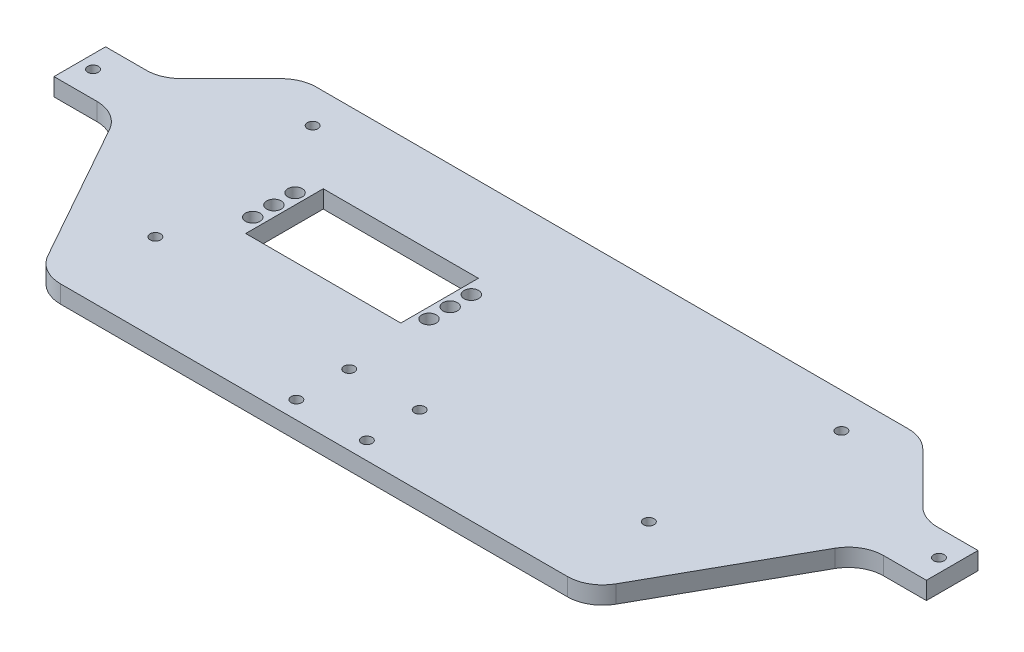
SolidWorks part; units mm, degrees
ref_plane "Alzado" through (0, 0, 0) normal (0, 0, 1) x (1, 0, 0)
ref_plane "Planta" through (0, 0, 0) normal (0, 1, 0) x (1, 0, 0)
ref_plane "Vista lateral" through (0, 0, 0) normal (1, 0, 0) x (0, 0, -1)
sketch "Croquis1" plane through (0, 0, 0) normal (0, 1, 0) x (1, 0, 0)
  line L0 (-27.8825, 0) -> (38.5584, 0) construction
  line L1 (-88.1, 42.3182) -> (88.1, 42.3182)
  line L2 (-77.75, -42.3182) -> (77.75, -42.3182)
  line L3 (-88.1, 42.3182) -> (-108.1, 22.3182)
  line L4 (-108.1, 22.3182) -> (-127.75, 22.3182)
  line L5 (0, 0) -> (0, 27.7067) construction
  line L6 (-127.75, 22.3182) -> (-127.75, 7.6818)
  line L7 (-127.75, 7.6818) -> (-105.75, 7.6818)
  line L8 (-105.75, 7.6818) -> (-77.75, -42.3182)
  line L9 (88.1, 42.3182) -> (108.1, 22.3182)
  line L10 (108.1, 22.3182) -> (127.75, 22.3182)
  line L11 (127.75, 22.3182) -> (127.75, 7.6818)
  line L12 (127.75, 7.6818) -> (105.75, 7.6818)
  line L13 (105.75, 7.6818) -> (77.75, -42.3182)
  dimension "D1" = 255.5
  dimension "D2" = 84.6363
  dimension "D3" = 19.65
  dimension "D4" = 22
  dimension "D5" = 22
  dimension "D6" = 50
  dimension "D7" = 50
  dimension "D8" = 50
  dimension "D9" = 20
  dimension "D10" = 20
  dimension "D11" = 19.65
extrude "Saliente-Extruir1" add sketch "Croquis1" along normal blind 5
fillet "Redondeo1" radius 10 8 edges at (88.1, 2.5, -42.3182) (-88.1, 2.5, -42.3182) (-77.75, 2.5, 42.3182) (77.75, 2.5, 42.3182) (108.1, 2.5, -22.3182) (105.75, 2.5, -7.6818) (-105.75, 2.5, -7.6818) (-108.1, 2.5, -22.3182)
sketch "Croquis2" plane through (0, 5, 0) normal (0, 1, 0) x (1, 0, 0)
  line L0 (0, 0) -> (0, -87.7887) construction
  line L1 (-119.9961, 22.3182) -> (-119.9961, 40.4374) construction
  line L2 (-112.2421, 22.3182) -> (-127.75, 22.3182) construction
  line L3 (-127.75, 15) -> (-123.2915, 15) construction
  line L4 (-127.75, 22.3182) -> (-127.75, 7.6818) construction
  line L5 (119.9961, 22.3182) -> (119.9961, 29.1715) construction
  line L6 (127.75, 22.3182) -> (112.2421, 22.3182) construction
  line L7 (115.6048, 15) -> (126.3231, 15) construction
  line L8 (83.9579, 42.3182) -> (-83.9579, 42.3182) construction
  line L9 (-57, 17.3182) -> (-15, 17.3182)
  line L10 (-71.8888, -42.3182) -> (71.8888, -42.3182) construction
  line L11 (-15, 17.3182) -> (-15, -2.6818)
  line L12 (-15, -2.6818) -> (-57, -2.6818)
  line L13 (-57, -2.6818) -> (-57, 17.3182)
  line L14 (-57, 7.3182) -> (-2.6959, 7.3182) construction
  line L15 (-36, 17.3182) -> (-36, 33.9331) construction
  line L16 (-11, 7.3182) -> (-11, 14.1752) construction
  line L17 (-61, 7.3182) -> (-61, 4.4352) construction
  circle A0 centre (70, -17.3182) radius 1.5
  circle A1 centre (-70, -17.3182) radius 1.5
  circle A2 centre (-119.9961, 15) radius 1.5
  circle A3 centre (119.9961, 15) radius 1.5
  circle A4 centre (-75, 32.3182) radius 1.5
  circle A5 centre (75, 32.3182) radius 1.5
  circle A6 centre (-10, -22.3182) radius 1.5
  circle A7 centre (10, -22.3182) radius 1.5
  circle A8 centre (-10, -37.3182) radius 1.5
  circle A9 centre (10, -37.3182) radius 1.5
  circle A10 centre (-61, 7.3182) radius 2.05
  circle A11 centre (-11, 7.3182) radius 2.05
  circle A12 centre (-61, 13.3182) radius 2.05
  circle A13 centre (-61, 1.3182) radius 2.05
  circle A14 centre (-11, 13.3182) radius 2.05
  circle A15 centre (-11, 1.3182) radius 2.05
  dimension "D1" = 3
  dimension "D2" = 3
  dimension "D7" = 3
  dimension "D8" = 3
  dimension "D10" = 3
  dimension "D11" = 3
  dimension "D17" = 3
  dimension "D18" = 3
  dimension "D19" = 3
  dimension "D20" = 3
  dimension "D25" = 50
  dimension "D27" = 4.1
  dimension "D28" = 4.1
  dimension "D29" = 4.1
  dimension "D30" = 4.1
  dimension "D31" = 4.1
  dimension "D32" = 4.1
  dimension "D3" = 75
  dimension "D4" = 75
  dimension "D5" = 10
  dimension "D6" = 10
  dimension "D9" = 140
  dimension "D12" = 25
  dimension "D13" = 20
  dimension "D14" = 20
  dimension "D15" = 5
  dimension "D16" = 15
  dimension "D21" = 42
  dimension "D22" = 20
  dimension "D23" = 30
  dimension "D24" = 25
  dimension "D26" = 50
  dimension "D33" = 6
  dimension "D34" = 6
  dimension "D35" = 6
  dimension "D36" = 6
extrude "Cortar-Extruir1" cut sketch "Croquis2" against normal through all
sketch "Croquis3" plane through (0, 5, 0) normal (0, 1, 0) x (1, 0, 0)
  line L0 (-123.75, 22.3182) -> (-123.75, 7.6818)
  line L1 (-112.2421, 22.3182) -> (-127.75, 22.3182) construction
  line L2 (-127.75, 7.6818) -> (-111.6112, 7.6818) construction
  line L3 (-123.75, 7.6818) -> (-127.75, 7.6818)
  line L4 (-127.75, 7.6818) -> (-127.75, 22.3182)
  line L5 (-127.75, 22.3182) -> (-123.75, 22.3182)
  line L6 (127.75, 7.6818) -> (127.75, 22.3182)
  line L7 (127.75, 22.3182) -> (123.75, 22.3182)
  line L8 (127.75, 22.3182) -> (112.2421, 22.3182) construction
  line L9 (123.75, 22.3182) -> (123.75, 7.6818)
  line L10 (111.6112, 7.6818) -> (127.75, 7.6818) construction
  line L11 (123.75, 7.6818) -> (127.75, 7.6818)
  dimension "D1" = 4
  dimension "D2" = 4
extrude "Cortar-Extruir2" cut sketch "Croquis3" against normal through all
sketch "Croquis4" plane through (0, 5, 0) normal (0, 1, 0) x (1, 0, 0)
  line L0 (-36, 17.3182) -> (-36, -16.9775) construction
  line L1 (-15, 17.3182) -> (-57, 17.3182) construction
  line L2 (-57, 7.3182) -> (-47.1795, 7.3182) construction
  line L3 (-57, 17.3182) -> (-57, -2.6818) construction
  line L4 (-58, 18.3182) -> (-58, -3.6818)
  line L5 (-58, -3.6818) -> (-14, -3.6818)
  line L6 (-14, -3.6818) -> (-14, 18.3182)
  line L7 (-58, 18.3182) -> (-14, 18.3182)
  line L8 (-15, -2.6818) -> (-15, 17.3182) construction
  line L9 (-57, -2.6818) -> (-15, -2.6818) construction
  dimension "D1" = 1
  dimension "D2" = 1
  dimension "D3" = 1
  dimension "D4" = 1
extrude "Cortar-Extruir3" cut sketch "Croquis4" against normal through all
